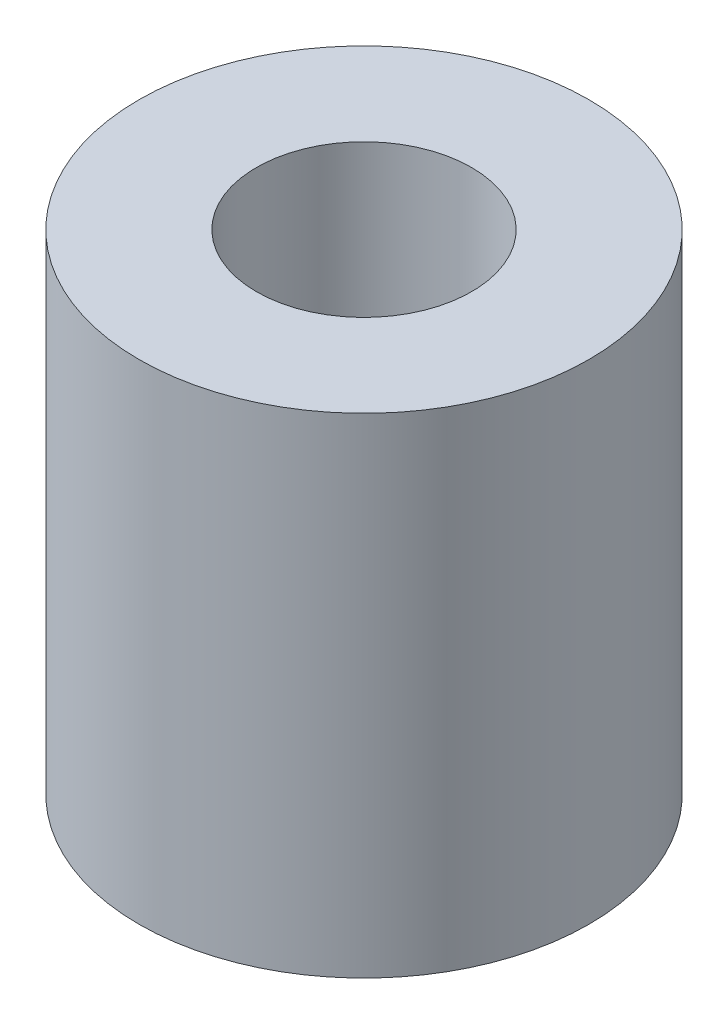
SolidWorks part; units mm, degrees
ref_plane "Alzado" through (0, 0, 0) normal (0, 0, 1) x (1, 0, 0)
ref_plane "Planta" through (0, 0, 0) normal (0, 1, 0) x (1, 0, 0)
ref_plane "Vista lateral" through (0, 0, 0) normal (1, 0, 0) x (0, 0, -1)
sketch "Croquis1" plane through (0, 0, 0) normal (0, 1, 0) x (1, 0, 0)
  circle A0 centre (0, 0) radius 11.5
  circle A1 centre (0, 0) radius 5.5
  dimension "D1" = 23
  dimension "D2" = 11
extrude "Saliente-Extruir1" add sketch "Croquis1" along normal blind 25
